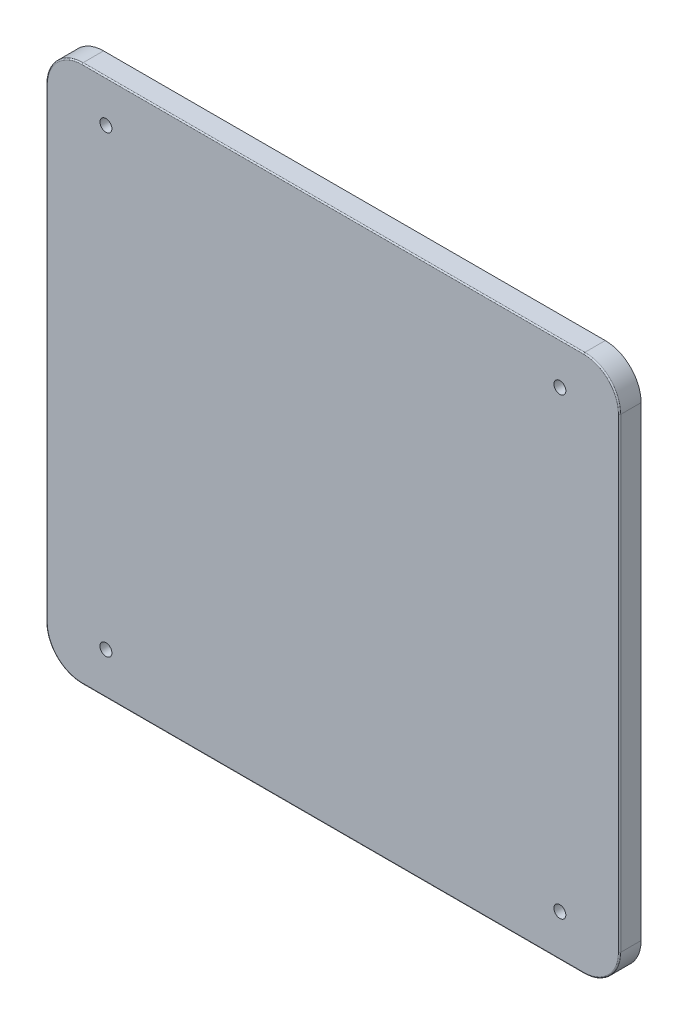
SolidWorks part; units mm, degrees
material "Buk"
ref_plane "Přední rovina" through (0, 0, 0) normal (0, 0, 1) x (1, 0, 0)
ref_plane "Vrchní rovina" through (0, 0, 0) normal (0, 1, 0) x (1, 0, 0)
ref_plane "Pravá rovina" through (0, 0, 0) normal (1, 0, 0) x (0, 0, -1)
sketch "Skica1" plane through (0, 0, 0) normal (0, 0, 1) x (1, 0, 0)
  line L1 (-210, 225) -> (210, 225)
  line L2 (-240, 195) -> (-240, -225)
  line L3 (-240, -225) -> (210, -225)
  line L4 (240, 195) -> (240, -195)
  line L5 (-240, 225) -> (240, -225) construction
  line L6 (-240, -225) -> (240, 225) construction
  arc A0 (210, -225) -> (240, -195) centre (210, -195) ccw
  arc A1 (210, 225) -> (240, 195) centre (210, 195) cw
  arc A2 (-210, 225) -> (-240, 195) centre (-210, 195) ccw
  point P0 (0, 0)
  dimension "D3" = 30
  dimension "D1" = 450
  dimension "D2" = 480
extrude "Přidat vysunutím1" add sketch "Skica1" along normal blind 18
sketch "Skica2" plane through (0, 0, 18) normal (0, 0, 1) x (1, 0, 0)
  line L0 (210, 225) -> (-210, 225) construction
  line L1 (-240, 195) -> (-240, -225) construction
  line L2 (-240, -225) -> (210, -225) construction
  line L3 (240, -195) -> (240, 195) construction
  point P0 (-190, 190)
  point P2 (190, 190)
  point P4 (190, -190)
  point P6 (-190, -190)
  point P15 (-349.9625, 128.2397)
  dimension "D1" = 35
  dimension "D2" = 50
  dimension "D3" = 50
  dimension "D4" = 35
  dimension "D5" = 50
  dimension "D6" = 35
  dimension "D7" = 50
  dimension "D8" = 35
hole_wizard "Díry pro kolík, Ø10.0mm1" positions "Skica2" profile "Skica4" hole size "Ø10.0" standard "ISO"
sketch "Skica4" plane through (-190, 190, 18) normal (1, 0, 0) x (0, -1, 0)
  line L0 (0, 0) -> (0, 13.0043)
  line L1 (0, 13.0043) -> (5, 10)
  line L2 (5, 10) -> (5, 0)
  line L5 (5, 0) -> (0, 0)
  line L10 (0, 13.0043) -> (-5, 10) construction
  line L11 (0, -6.35) -> (0, 107.95) construction
  dimension "Průměr díry" = 10
  dimension "Hloubka díry" = 10
  dimension "Úhel vrtání" = 118
fillet "Zaoblit1" radius 30 1 edges at (-240, -225, 9)
fillet "Zaoblit2" radius 1 8 edges at (231.2132, -216.2132, 18) (0, -225, 18) (-231.2132, -216.2132, 18) (-240, 0, 18) (-231.2132, 216.2132, 18) (0, 225, 18) (231.2132, 216.2132, 18) (240, 0, 18)
